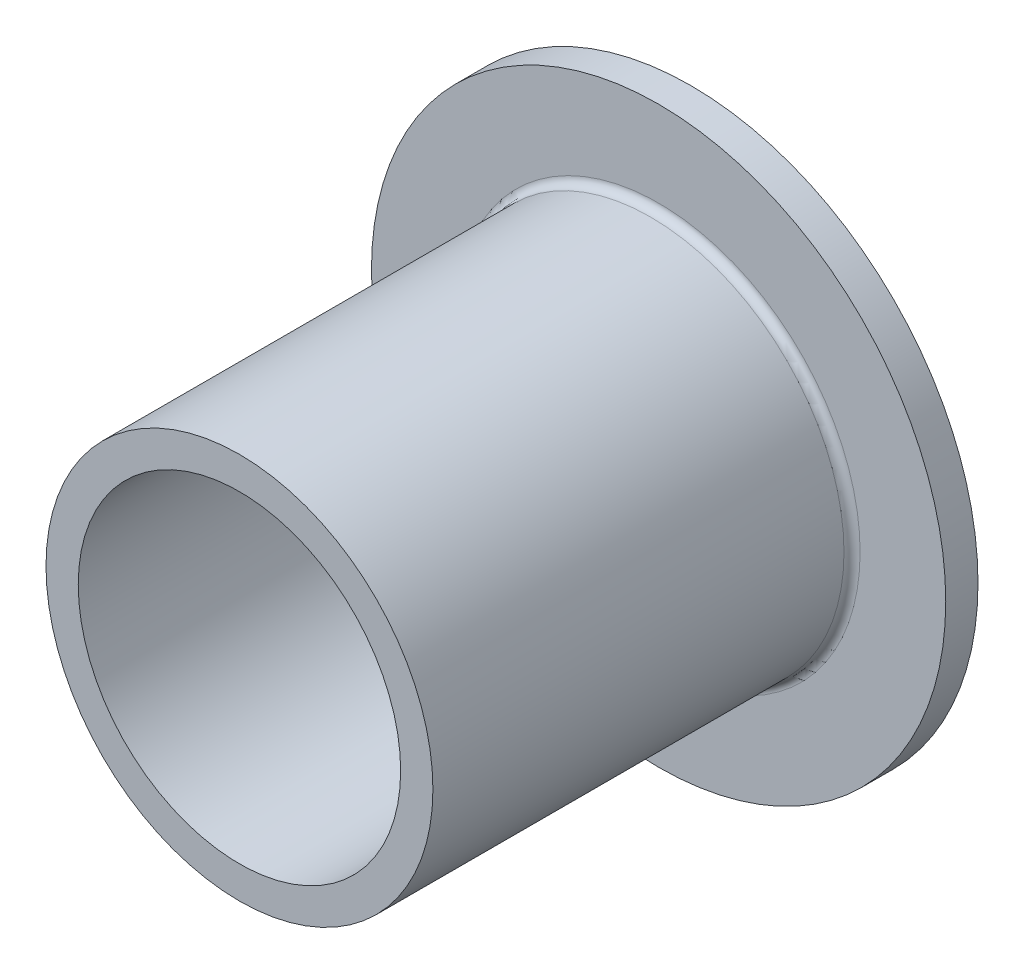
SolidWorks part; units mm, degrees
material "Cast Alloy Steel"
ref_plane "Front Plane" through (0, 0, 0) normal (0, 0, 1) x (1, 0, 0)
ref_plane "Top Plane" through (0, 0, 0) normal (0, 1, 0) x (1, 0, 0)
ref_plane "Right Plane" through (0, 0, 0) normal (1, 0, 0) x (0, 0, -1)
sketch "Sketch1" plane through (0, 0, 0) normal (0, 0, 1) x (1, 0, 0)
  circle A0 centre (0, 0) radius 35.625
  circle A1 centre (0, 0) radius 20
  dimension "D1" = 40
  dimension "D2" = 71.25
extrude "Boss-Extrude1" add sketch "Sketch1" along normal blind 4
sketch "Sketch2" plane through (0, 0, 4) normal (0, 0, 1) x (1, 0, 0)
  circle A0 centre (0, 0) radius 20 construction
  circle A1 centre (0, 0) radius 20
  circle A2 centre (0, 0) radius 24
  dimension "D1" = 4
extrude "Boss-Extrude2" add sketch "Sketch2" along normal blind 52
sketch "Sketch3" plane through (0, 0, 0) normal (0, 1, 0) x (1, 0, 0)
  line L0 (-20, -56) -> (20, -56) construction
  line L1 (-46.75, -30) -> (-31.75, -30)
  line L2 (-46.75, -30) -> (-46.75, -38)
  line L3 (-46.75, -38) -> (-31.75, -38)
  line L4 (-31.75, -30) -> (-31.75, -38)
  line L5 (11.25, 0) -> (19.25, 0)
  line L6 (11.25, 0) -> (11.25, -38)
  line L7 (11.25, -38) -> (19.25, -38)
  line L8 (19.25, 0) -> (19.25, -38)
  line L9 (20, 0) -> (-20, 0) construction
  line L10 (-31.75, -30) -> (-20, -41.75)
  line L11 (-20, -56) -> (-20, 0)
  dimension "D1" = 8
  dimension "D2" = 15
  dimension "D3" = 18
  dimension "D4" = 43
  dimension "D5" = 11.25
  dimension "D6" = 8
  dimension "D7" = 18
  dimension "D8" = 45
fillet "Fillet1" radius 1 1 edges at (24, 0, 4)
